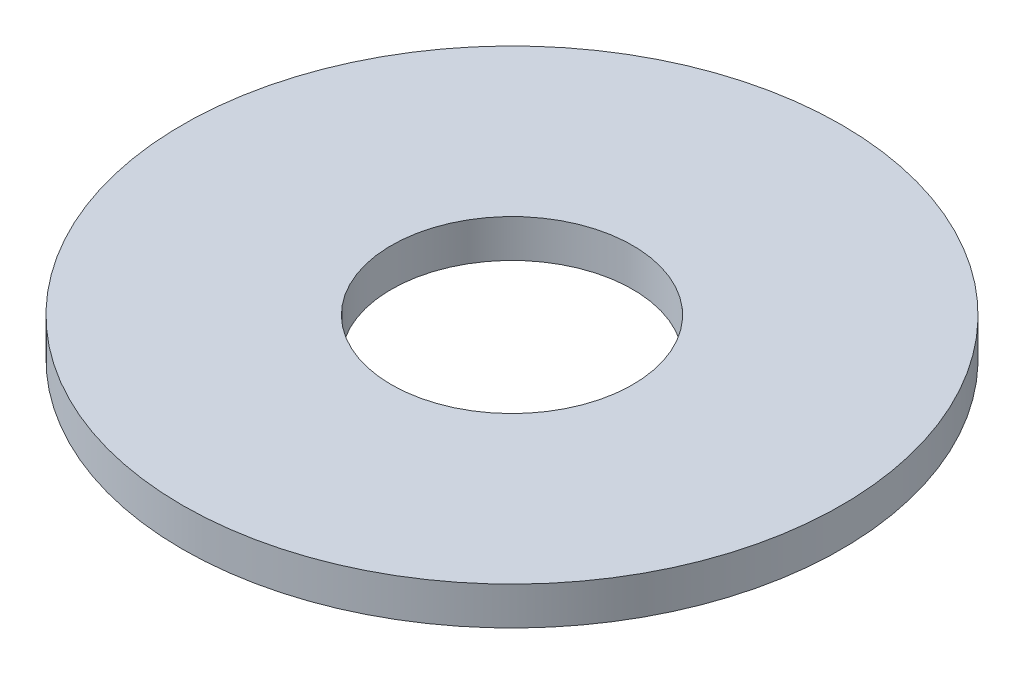
SolidWorks part; units mm, degrees
material "AISI 304"
ref_plane "Plano frontal" through (0, 0, 0) normal (0, 0, 1) x (1, 0, 0)
ref_plane "Plano superior" through (0, 0, 0) normal (0, 1, 0) x (1, 0, 0)
ref_plane "Plano direito" through (0, 0, 0) normal (1, 0, 0) x (0, 0, -1)
sketch "Esboço1" plane through (0, 0, 0) normal (0, 1, 0) x (1, 0, 0)
  circle A0 centre (0, 0) radius 4.76
  circle A1 centre (0, 0) radius 13
  dimension "D1" = 26
  dimension "D2" = 9.52
extrude "Ressalto-extrusão1" add sketch "Esboço1" along normal mid plane 1.5
